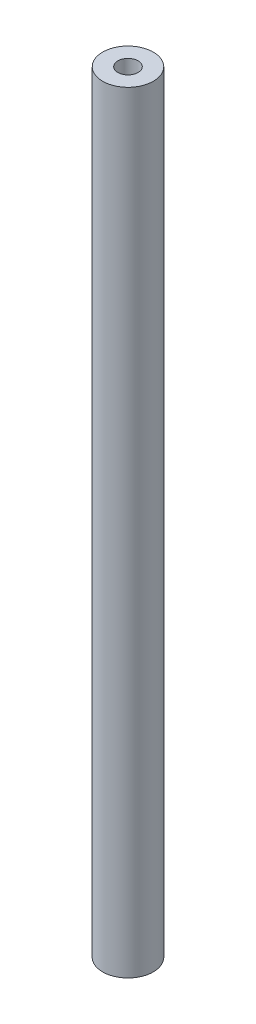
SolidWorks part; units mm, degrees
ref_plane "Front Plane" through (0, 0, 0) normal (0, 0, 1) x (1, 0, 0)
ref_plane "Top Plane" through (0, 0, 0) normal (0, 1, 0) x (1, 0, 0)
ref_plane "Right Plane" through (0, 0, 0) normal (1, 0, 0) x (0, 0, -1)
sketch "Sketch1" plane through (0, 0, 0) normal (0, 1, 0) x (1, 0, 0)
  circle A0 centre (0, 0) radius 15
  circle A1 centre (0, 0) radius 6
  dimension "D1" = 30
  dimension "D2" = 12
extrude "Boss-Extrude1" add sketch "Sketch1" along normal mid plane 457.2
